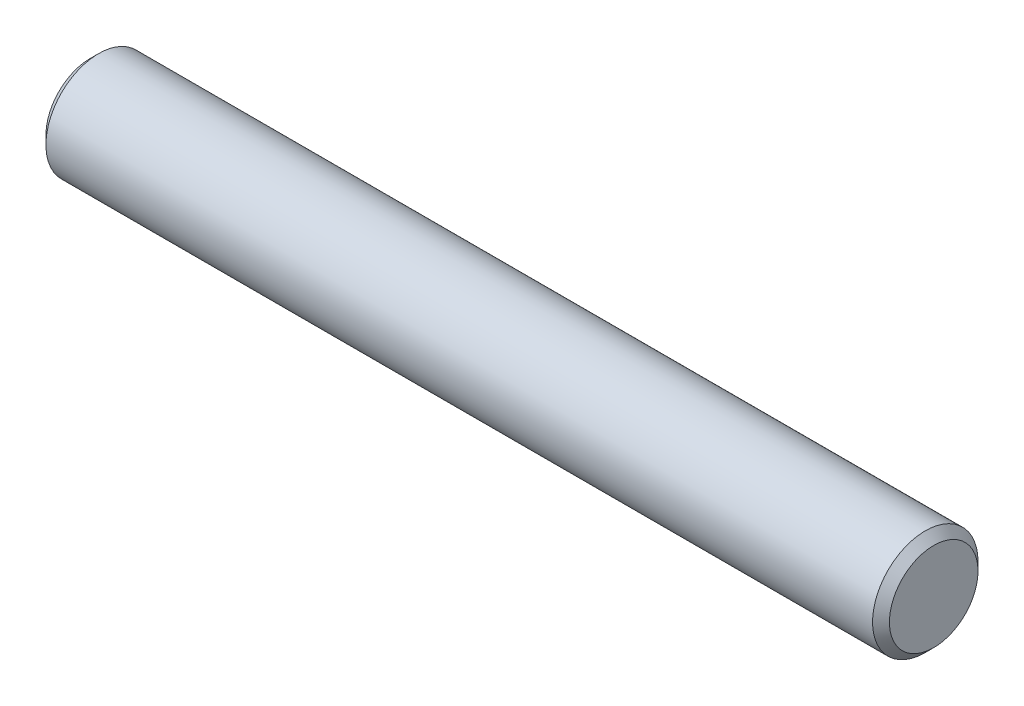
SolidWorks part; units mm, degrees
ref_plane "Front Plane" through (0, 0, 0) normal (0, 0, 1) x (1, 0, 0)
ref_plane "Top Plane" through (0, 0, 0) normal (0, 1, 0) x (1, 0, 0)
ref_plane "Right Plane" through (0, 0, 0) normal (1, 0, 0) x (0, 0, -1)
sketch "Sketch1" plane through (0, 0, 0) normal (0, 1, 0) x (1, 0, 0)
  line L0 (-100, 0) -> (100, 0)
  point P3 (0, 0)
  dimension "D1" = 200
sketch "Sketch2" plane through (0, 0, 0) normal (1, 0, 0) x (0, 0, -1)
  circle A0 centre (0, 0) radius 12.5
  dimension "D1" = 25
sweep "Sweep1" add profiles "Sketch2" path "Sketch1"
chamfer "Chamfer1" distance 2 angle 45 2 edges at (100, 0, -12.5) (-100, 0, -12.5)
